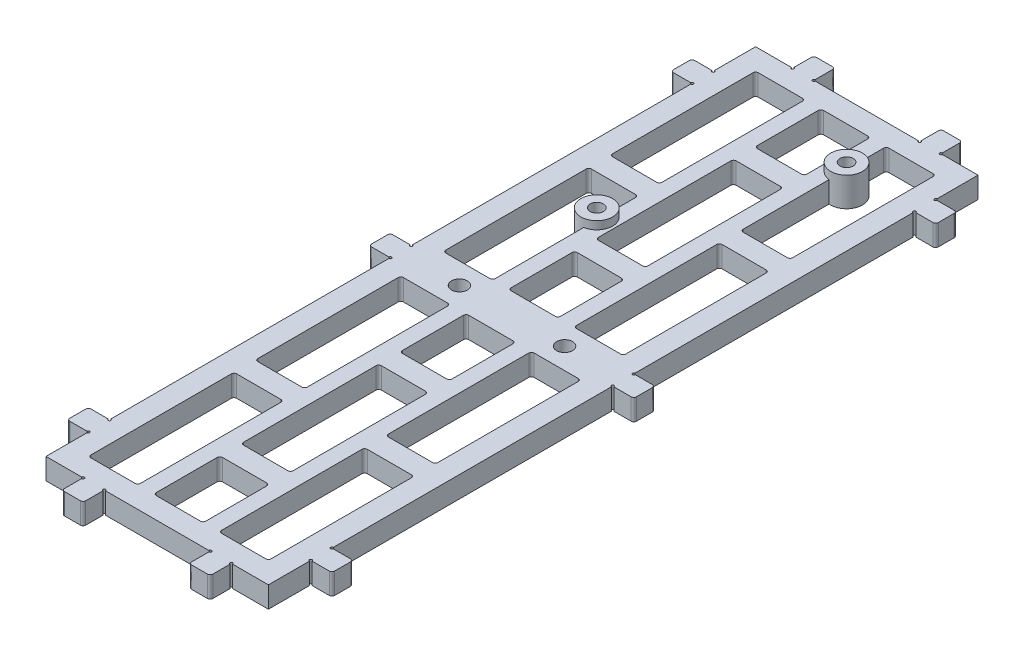
SolidWorks part; units mm, degrees
ref_plane "前视基准面" through (0, 0, 0) normal (0, 0, 1) x (1, 0, 0)
ref_plane "上视基准面" through (0, 0, 0) normal (0, 1, 0) x (1, 0, 0)
ref_plane "右视基准面" through (0, 0, 0) normal (1, 0, 0) x (0, 0, -1)
sketch "草图1" plane through (0, 0, 0) normal (0, 1, 0) x (1, 0, 0)
  line L0 (0, 0) -> (9.925, 0) construction
  line L1 (-21, 67) -> (21, 67)
  line L2 (-21, 67) -> (-21, -67)
  line L3 (-21, -67) -> (21, -67)
  line L4 (21, 67) -> (21, -67)
  line L5 (-21, 67) -> (21, -67) construction
  line L6 (-21, -67) -> (21, 67) construction
  line L7 (0, 0) -> (0, 13.0607) construction
  circle A0 centre (9.925, 0) radius 1.5
  circle A1 centre (-9.925, 0) radius 1.5
  point P0 (0, 0)
  dimension "D3" = 3
  dimension "D1" = 42
  dimension "D2" = 134
  dimension "D4" = 19.85
extrude "凸台-拉伸1" add sketch "草图1" along normal mid plane 4
sketch "草图4" plane through (0, 2, 0) normal (0, 1, 0) x (1, 0, 0)
  line L0 (0, 0) -> (0, -33.5) construction
  line L1 (-16.5, -4) -> (-8.17, -4)
  line L2 (-17, -4.5) -> (-17, -31)
  line L3 (-16.5, -31.5) -> (-8.17, -31.5)
  line L4 (-7.67, -4.5) -> (-7.67, -31)
  line L5 (-17, -4) -> (-7.67, -31.5) construction
  line L6 (-17, -31.5) -> (-7.67, -4) construction
  line L7 (16.5, -4) -> (8.17, -4)
  line L8 (17, -4.5) -> (17, -31)
  line L9 (16.5, -31.5) -> (8.17, -31.5)
  line L10 (7.67, -4.5) -> (7.67, -31)
  line L11 (0, -33.5) -> (28.1016, -33.5) construction
  line L12 (-16.5, -63) -> (-8.17, -63)
  line L13 (-17, -62.5) -> (-17, -36)
  line L14 (-16.5, -35.5) -> (-8.17, -35.5)
  line L15 (-7.67, -62.5) -> (-7.67, -36)
  line L16 (16.5, -63) -> (8.17, -63)
  line L17 (17, -62.5) -> (17, -36)
  line L18 (16.5, -35.5) -> (8.17, -35.5)
  line L19 (7.67, -62.5) -> (7.67, -36)
  line L20 (-4.67, -62.5) -> (-4.67, -51)
  line L21 (-4.17, -20.5) -> (4.17, -20.5)
  line L22 (-4.67, -21) -> (-4.67, -46)
  line L23 (-4.17, -46.5) -> (4.17, -46.5)
  line L24 (4.67, -21) -> (4.67, -46)
  line L25 (-4.67, -20.5) -> (4.67, -46.5) construction
  line L26 (-4.67, -46.5) -> (4.67, -20.5) construction
  line L27 (-4.17, -4) -> (4.17, -4)
  line L28 (-4.67, -4.5) -> (-4.67, -16)
  line L29 (-4.17, -16.5) -> (4.17, -16.5)
  line L30 (4.67, -4.5) -> (4.67, -16)
  line L31 (-4.67, -4) -> (4.67, -16.5) construction
  line L32 (-4.67, -16.5) -> (4.67, -4) construction
  line L33 (-4.17, -63) -> (4.17, -63)
  line L34 (4.67, -62.5) -> (4.67, -51)
  line L35 (-4.17, -50.5) -> (4.17, -50.5)
  line L36 (21, -67) -> (21, 67) construction
  line L37 (0, 0) -> (-24.9433, 0) construction
  line L38 (-4.17, 63) -> (4.17, 63)
  line L39 (4.67, 62.5) -> (4.67, 51)
  line L40 (-4.17, 50.5) -> (4.17, 50.5)
  line L41 (-4.67, 62.5) -> (-4.67, 51)
  line L42 (-17, 62.5) -> (-17, 36)
  line L43 (-16.5, 35.5) -> (-8.17, 35.5)
  line L44 (-7.67, 62.5) -> (-7.67, 36)
  line L45 (-16.5, 63) -> (-8.17, 63)
  line L46 (-16.5, 31.5) -> (-8.17, 31.5)
  line L47 (-7.67, 4.5) -> (-7.67, 31)
  line L48 (-16.5, 4) -> (-8.17, 4)
  line L49 (-17, 4.5) -> (-17, 31)
  line L50 (-4.17, 16.5) -> (4.17, 16.5)
  line L51 (4.67, 4.5) -> (4.67, 16)
  line L52 (-4.17, 4) -> (4.17, 4)
  line L53 (-4.67, 4.5) -> (-4.67, 16)
  line L54 (-4.17, 46.5) -> (4.17, 46.5)
  line L55 (4.67, 21) -> (4.67, 46)
  line L56 (-4.17, 20.5) -> (4.17, 20.5)
  line L57 (-4.67, 21) -> (-4.67, 46)
  line L58 (17, 4.5) -> (17, 31)
  line L59 (16.5, 31.5) -> (8.17, 31.5)
  line L60 (7.67, 4.5) -> (7.67, 31)
  line L61 (16.5, 4) -> (8.17, 4)
  line L62 (17, 62.5) -> (17, 36)
  line L63 (16.5, 35.5) -> (8.17, 35.5)
  line L64 (7.67, 62.5) -> (7.67, 36)
  line L65 (16.5, 63) -> (8.17, 63)
  arc A0 (-16.5, -63) -> (-17, -62.5) centre (-16.5, -62.5) cw
  arc A1 (-8.17, -63) -> (-7.67, -62.5) centre (-8.17, -62.5) ccw
  arc A2 (-17, -36) -> (-16.5, -35.5) centre (-16.5, -36) cw
  arc A3 (-8.17, -35.5) -> (-7.67, -36) centre (-8.17, -36) cw
  arc A4 (-17, -31) -> (-16.5, -31.5) centre (-16.5, -31) ccw
  arc A5 (-8.17, -31.5) -> (-7.67, -31) centre (-8.17, -31) ccw
  arc A6 (-16.5, -4) -> (-17, -4.5) centre (-16.5, -4.5) ccw
  arc A7 (-8.17, -4) -> (-7.67, -4.5) centre (-8.17, -4.5) cw
  arc A8 (-4.17, -4) -> (-4.67, -4.5) centre (-4.17, -4.5) ccw
  arc A9 (4.17, -4) -> (4.67, -4.5) centre (4.17, -4.5) cw
  arc A10 (-4.67, -16) -> (-4.17, -16.5) centre (-4.17, -16) ccw
  arc A11 (4.17, -16.5) -> (4.67, -16) centre (4.17, -16) ccw
  arc A12 (-4.17, -20.5) -> (-4.67, -21) centre (-4.17, -21) ccw
  arc A13 (4.17, -20.5) -> (4.67, -21) centre (4.17, -21) cw
  arc A14 (-4.67, -46) -> (-4.17, -46.5) centre (-4.17, -46) ccw
  arc A15 (4.17, -46.5) -> (4.67, -46) centre (4.17, -46) ccw
  arc A16 (-4.67, -51) -> (-4.17, -50.5) centre (-4.17, -51) cw
  arc A17 (4.67, -51) -> (4.17, -50.5) centre (4.17, -51) ccw
  arc A18 (-4.67, -62.5) -> (-4.17, -63) centre (-4.17, -62.5) ccw
  arc A19 (4.17, -63) -> (4.67, -62.5) centre (4.17, -62.5) ccw
  arc A20 (16.5, -63) -> (17, -62.5) centre (16.5, -62.5) ccw
  arc A21 (8.17, -63) -> (7.67, -62.5) centre (8.17, -62.5) cw
  arc A22 (8.17, -35.5) -> (7.67, -36) centre (8.17, -36) ccw
  arc A23 (17, -36) -> (16.5, -35.5) centre (16.5, -36) ccw
  arc A24 (17, -31) -> (16.5, -31.5) centre (16.5, -31) cw
  arc A25 (8.17, -31.5) -> (7.67, -31) centre (8.17, -31) cw
  arc A26 (8.17, -4) -> (7.67, -4.5) centre (8.17, -4.5) ccw
  arc A27 (16.5, -4) -> (17, -4.5) centre (16.5, -4.5) cw
  arc A28 (4.17, 63) -> (4.67, 62.5) centre (4.17, 62.5) cw
  arc A29 (4.67, 51) -> (4.17, 50.5) centre (4.17, 51) cw
  arc A30 (-4.67, 51) -> (-4.17, 50.5) centre (-4.17, 51) ccw
  arc A31 (-4.67, 62.5) -> (-4.17, 63) centre (-4.17, 62.5) cw
  arc A32 (-17, 36) -> (-16.5, 35.5) centre (-16.5, 36) ccw
  arc A33 (-8.17, 35.5) -> (-7.67, 36) centre (-8.17, 36) ccw
  arc A34 (-16.5, 63) -> (-17, 62.5) centre (-16.5, 62.5) ccw
  arc A35 (-8.17, 63) -> (-7.67, 62.5) centre (-8.17, 62.5) cw
  arc A36 (-8.17, 31.5) -> (-7.67, 31) centre (-8.17, 31) cw
  arc A37 (-8.17, 4) -> (-7.67, 4.5) centre (-8.17, 4.5) ccw
  arc A38 (-17, 31) -> (-16.5, 31.5) centre (-16.5, 31) cw
  arc A39 (-16.5, 4) -> (-17, 4.5) centre (-16.5, 4.5) cw
  arc A40 (4.17, 16.5) -> (4.67, 16) centre (4.17, 16) cw
  arc A41 (4.17, 4) -> (4.67, 4.5) centre (4.17, 4.5) ccw
  arc A42 (-4.17, 4) -> (-4.67, 4.5) centre (-4.17, 4.5) cw
  arc A43 (-4.67, 16) -> (-4.17, 16.5) centre (-4.17, 16) cw
  arc A44 (4.17, 46.5) -> (4.67, 46) centre (4.17, 46) cw
  arc A45 (4.17, 20.5) -> (4.67, 21) centre (4.17, 21) ccw
  arc A46 (-4.17, 20.5) -> (-4.67, 21) centre (-4.17, 21) cw
  arc A47 (-4.67, 46) -> (-4.17, 46.5) centre (-4.17, 46) cw
  arc A48 (17, 31) -> (16.5, 31.5) centre (16.5, 31) ccw
  arc A49 (8.17, 31.5) -> (7.67, 31) centre (8.17, 31) ccw
  arc A50 (8.17, 4) -> (7.67, 4.5) centre (8.17, 4.5) cw
  arc A51 (16.5, 4) -> (17, 4.5) centre (16.5, 4.5) ccw
  arc A52 (17, 36) -> (16.5, 35.5) centre (16.5, 36) cw
  arc A53 (8.17, 35.5) -> (7.67, 36) centre (8.17, 36) cw
  arc A54 (16.5, 63) -> (17, 62.5) centre (16.5, 62.5) cw
  arc A55 (8.17, 63) -> (7.67, 62.5) centre (8.17, 62.5) ccw
  point P0 (-12.335, -17.75)
  point P25 (0, -10.25)
  point P38 (-17, -63)
  point P42 (-7.67, -63)
  point P45 (-17, -35.5)
  point P48 (-7.67, -35.5)
  point P87 (-4.67, -50.5)
  point P90 (4.67, -50.5)
  point P93 (-4.67, -63)
  point P96 (4.67, -63)
  point P99 (17, -63)
  point P102 (7.67, -63)
  point P105 (7.67, -35.5)
  point P108 (17, -35.5)
  point P111 (17, -31.5)
  point P114 (7.67, -31.5)
  point P117 (7.67, -4)
  point P120 (17, -4)
  dimension "D9" = 0.5
  dimension "D1" = 33.5
  dimension "D2" = 4
  dimension "D3" = 4
  dimension "D4" = 3
  dimension "D5" = 4
  dimension "D6" = 9.33
  dimension "D7" = 4
  dimension "D8" = 26
sketch "草图2" plane through (0, 2, 0) normal (0, 1, 0) x (1, 0, 0)
  circle A0 centre (7.98, 55.2) radius 1.65 construction
  circle A1 centre (-8.1615, 24.1719) radius 1.65 construction
  circle A2 centre (7.98, 55.2) radius 1.65 construction
  circle A3 centre (-8.1615, 24.1719) radius 1.65 construction
  circle A4 centre (7.98, 55.2) radius 3
  circle A6 centre (-8.1615, 24.1719) radius 3
  dimension "D1" = 6
  dimension "D2" = 6
sketch "草图3" plane through (0, 2, 0) normal (0, 1, 0) x (1, 0, 0)
  circle A0 centre (-8.1615, 24.1719) radius 1.25
  circle A1 centre (7.98, 55.2) radius 1.25
  dimension "D1" = 2.5
  dimension "D2" = 2.5
extrude "切除-拉伸4" cut sketch "草图4" against normal blind 4
extrude "凸台-拉伸3" add sketch "草图2" along normal blind 1.5 and the other way blind 4
extrude "切除-拉伸5" cut sketch "草图3" against normal through all both and the other way through all
sketch "草图5" plane through (0, 2, 0) normal (0, 1, 0) x (1, 0, 0)
  line L0 (0, 0) -> (23, 0) construction
  line L1 (21, 2) -> (24.5, 2)
  line L2 (21, 2) -> (21, -2)
  line L3 (21, -2) -> (24.5, -2)
  line L4 (25, 1.5) -> (25, -1.5)
  line L5 (21, 2) -> (25, -2) construction
  line L6 (21, -2) -> (25, 2) construction
  line L7 (21, -67) -> (21, 67) construction
  line L8 (21, -55) -> (24.5, -55)
  line L9 (21, 59) -> (24.5, 59)
  line L10 (21, 59) -> (21, 55)
  line L11 (21, 55) -> (24.5, 55)
  line L12 (25, 58.5) -> (25, 55.5)
  line L13 (21, 59) -> (25, 55) construction
  line L14 (21, 55) -> (25, 59) construction
  line L15 (25, -58.5) -> (25, -55.5)
  line L16 (21, -59) -> (24.5, -59)
  line L17 (21, -59) -> (21, -55)
  line L18 (0, 0) -> (0, 7.9849) construction
  line L19 (-21, 55) -> (-24.5, 55)
  line L20 (-25, 58.5) -> (-25, 55.5)
  line L21 (-21, 59) -> (-24.5, 59)
  line L22 (-21, 59) -> (-21, 55)
  line L23 (-21, -2) -> (-24.5, -2)
  line L24 (-25, 1.5) -> (-25, -1.5)
  line L25 (-21, 2) -> (-24.5, 2)
  line L26 (-21, 2) -> (-21, -2)
  line L27 (-21, -59) -> (-21, -55)
  line L28 (-21, -59) -> (-24.5, -59)
  line L29 (-25, -58.5) -> (-25, -55.5)
  line L30 (-21, -55) -> (-24.5, -55)
  line L31 (21, 67) -> (-21, 67) construction
  line L32 (-13.5, 71) -> (-10.5, 71)
  line L33 (-14, 70.5) -> (-14, 67)
  line L34 (-14, 67) -> (-10, 67)
  line L35 (-10, 70.5) -> (-10, 67)
  line L36 (-14, 71) -> (-10, 67) construction
  line L37 (-14, 67) -> (-10, 71) construction
  line L38 (14, 67) -> (10, 67)
  line L39 (10, 70.5) -> (10, 67)
  line L40 (13.5, 71) -> (10.5, 71)
  line L41 (14, 70.5) -> (14, 67)
  line L42 (-14, -67) -> (-10, -67)
  line L43 (-10, -70.5) -> (-10, -67)
  line L44 (-13.5, -71) -> (-10.5, -71)
  line L45 (-14, -70.5) -> (-14, -67)
  line L46 (13.5, -71) -> (10.5, -71)
  line L47 (14, -70.5) -> (14, -67)
  line L48 (14, -67) -> (10, -67)
  line L49 (10, -70.5) -> (10, -67)
  arc A0 (24.5, -2) -> (25, -1.5) centre (24.5, -1.5) ccw
  arc A1 (24.5, 2) -> (25, 1.5) centre (24.5, 1.5) cw
  arc A2 (24.5, 55) -> (25, 55.5) centre (24.5, 55.5) ccw
  arc A3 (24.5, 59) -> (25, 58.5) centre (24.5, 58.5) cw
  arc A4 (25, -58.5) -> (24.5, -59) centre (24.5, -58.5) cw
  arc A5 (24.5, -55) -> (25, -55.5) centre (24.5, -55.5) cw
  arc A6 (-24.5, 55) -> (-25, 55.5) centre (-24.5, 55.5) cw
  arc A7 (-24.5, 59) -> (-25, 58.5) centre (-24.5, 58.5) ccw
  arc A8 (-24.5, -2) -> (-25, -1.5) centre (-24.5, -1.5) cw
  arc A9 (-24.5, 2) -> (-25, 1.5) centre (-24.5, 1.5) ccw
  arc A10 (-25, -58.5) -> (-24.5, -59) centre (-24.5, -58.5) ccw
  arc A11 (-24.5, -55) -> (-25, -55.5) centre (-24.5, -55.5) ccw
  arc A12 (-10.5, 71) -> (-10, 70.5) centre (-10.5, 70.5) cw
  arc A13 (-13.5, 71) -> (-14, 70.5) centre (-13.5, 70.5) ccw
  arc A14 (10.5, 71) -> (10, 70.5) centre (10.5, 70.5) ccw
  arc A15 (13.5, 71) -> (14, 70.5) centre (13.5, 70.5) cw
  arc A16 (-10.5, -71) -> (-10, -70.5) centre (-10.5, -70.5) ccw
  arc A17 (-13.5, -71) -> (-14, -70.5) centre (-13.5, -70.5) cw
  arc A18 (13.5, -71) -> (14, -70.5) centre (13.5, -70.5) ccw
  arc A19 (10.5, -71) -> (10, -70.5) centre (10.5, -70.5) cw
  point P0 (23, 0)
  point P16 (23, 57)
  point P33 (25, -59)
  point P36 (25, -55)
  point P62 (-12, 69)
  dimension "D3" = 0.5
  dimension "D7" = 0.5
  dimension "D10" = 0.5
  dimension "D1" = 4
  dimension "D2" = 4
  dimension "D4" = 4
  dimension "D5" = 4
  dimension "D6" = 110
  dimension "D8" = 4
  dimension "D9" = 4
  dimension "D11" = 20
extrude "凸台-拉伸4" add sketch "草图5" against normal through all
sketch "草图6" plane through (0, 2, 0) normal (0, 1, 0) x (1, 0, 0)
  line L0 (0, 0) -> (0, 7.1915) construction
  line L1 (0, 0) -> (5.6698, 0) construction
  circle A0 centre (21, 59) radius 0.25
  circle A1 centre (21, 55) radius 0.25
  circle A2 centre (21, 2) radius 0.25
  circle A3 centre (21, -2) radius 0.25
  circle A4 centre (21, -55) radius 0.25
  circle A5 centre (21, -59) radius 0.25
  circle A6 centre (14, 67) radius 0.25
  circle A7 centre (10, 67) radius 0.25
  circle A8 centre (10, -67) radius 0.25
  circle A9 centre (14, -67) radius 0.25
  circle A10 centre (-14, -67) radius 0.25
  circle A11 centre (-10, -67) radius 0.25
  circle A12 centre (-10, 67) radius 0.25
  circle A13 centre (-14, 67) radius 0.25
  circle A14 centre (-21, -59) radius 0.25
  circle A15 centre (-21, -55) radius 0.25
  circle A16 centre (-21, -2) radius 0.25
  circle A17 centre (-21, 2) radius 0.25
  circle A18 centre (-21, 55) radius 0.25
  circle A19 centre (-21, 59) radius 0.25
  dimension "D1" = 0.5
  dimension "D2" = 0.5
  dimension "D3" = 0.5
  dimension "D4" = 0.5
  dimension "D5" = 0.5
  dimension "D6" = 0.5
  dimension "D7" = 0.5
  dimension "D8" = 0.5
extrude "切除-拉伸6" cut sketch "草图6" against normal through all both
